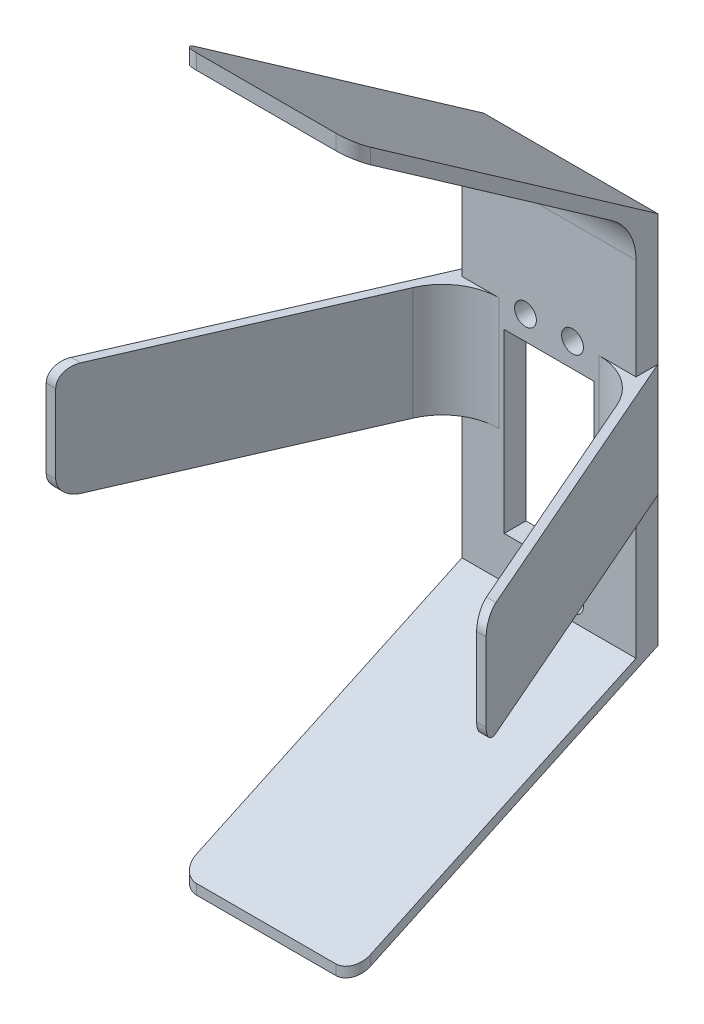
SolidWorks part; units mm, degrees
ref_plane "Plan de face" through (0, 0, 0) normal (0, 0, 1) x (1, 0, 0)
ref_plane "Plan de dessus" through (0, 0, 0) normal (0, 1, 0) x (1, 0, 0)
ref_plane "Plan de droite" through (0, 0, 0) normal (1, 0, 0) x (0, 0, -1)
sketch "Esquisse1" plane through (0, 0, 0) normal (0, 0, 1) x (1, 0, 0)
  line L8 (0.3, -20.3) -> (0.3, 20.3)
  line L9 (0.3, 20.3) -> (-20.3, 20.3)
  line L10 (-20.3, 20.3) -> (-20.3, -20.3)
  line L11 (-20.3, -20.3) -> (0.3, -20.3)
  line L12 (0.3, -20.3) -> (0.3, 20.3)
  line L13 (0.3, 20.3) -> (-20.3, 20.3)
  line L14 (-20.3, 20.3) -> (-20.3, -20.3)
  line L15 (-20.3, -20.3) -> (0.3, -20.3)
  line L20 (10, -30) -> (10, 30)
  line L21 (10, 30) -> (-30, 30)
  line L22 (-30, 30) -> (-30, -30)
  line L23 (-30, -30) -> (10, -30)
  line L24 (10, -30) -> (10, 30)
  line L25 (10, 30) -> (-30, 30)
  line L26 (-30, 30) -> (-30, -30)
  line L27 (-30, -30) -> (10, -30)
  dimension "D1" = 0.3
  dimension "D2" = 10
extrude "Boss.-Extru.1" add sketch "Esquisse1" along normal blind 5
sketch "Esquisse2" plane through (0, 30, 0) normal (0, 1, 0) x (1, 0, 0)
  line L4 (10, 0) -> (-30, 0)
  line L5 (-30, 0) -> (-30, -5)
  line L6 (-30, -5) -> (10, -5)
  line L7 (10, -5) -> (10, 0)
  line L8 (10, 0) -> (-30, 0)
  line L9 (-30, 0) -> (-30, -5)
  line L10 (-30, -5) -> (10, -5)
  line L11 (10, -5) -> (10, 0)
  dimension "D1" = 0
extrude "Boss.-Extru.2" add sketch "Esquisse2" along normal blind 26
sketch "Esquisse3" plane through (10, 0, 0) normal (1, 0, 0) x (0, 0, -1)
  line L0 (0, 56) -> (-70, 105.0145)
  line L1 (-70, 105.0145) -> (-70, 101.5135)
  line L2 (-70, 101.5135) -> (-5, 56)
  line L3 (-5, 56) -> (0, 56) construction
  line L5 (-5, 56) -> (0, 56)
  line L6 (-5, -30) -> (-5, 56) construction
  line L7 (-5, -30) -> (0, -30) construction
  line L8 (-5, -30) -> (0, -30)
  line L9 (-5, -30) -> (-70, -60.31)
  line L10 (-70, -60.31) -> (-70, -62.6415)
  line L11 (-70, -62.6415) -> (0, -30)
  point P7 (-70, 103.264)
  dimension "D1" = 125
  dimension "D2" = 65
  dimension "D3" = 115
extrude "Boss.-Extru.5" add sketch "Esquisse3" against normal up to surface (40 mm away) up to face at (-30, 13, 2.5)
sketch "Esquisse4" plane through (0, 0, 0) normal (0, 1, 0) x (1, 0, 0)
  line L0 (-30, -5) -> (-58.3683, -70)
  line L1 (-58.3683, -70) -> (-60.5505, -70)
  line L2 (-60.5505, -70) -> (-30, 0)
  line L3 (-30, -70) -> (-30, 0) construction
  line L5 (10, 0) -> (40.5505, -70)
  line L6 (40.5505, -70) -> (38.3683, -70)
  line L7 (38.3683, -70) -> (10, -5)
  line L8 (10, -5) -> (10, 0)
  line L9 (-30, -70) -> (10, -70) construction
  line L10 (-30, 0) -> (-30, -5)
  line L11 (10, 0) -> (-30, 0) construction
  point P15 (0, 0)
  dimension "D1" = 2
  dimension "D2" = 2
extrude "Boss.-Extru.6" add sketch "Esquisse4" along normal blind 26
fillet "Congé1" radius 13 3 edges at (-10, 56, 5) (10, 13, 5) (-30, 13, 5)
fillet "Congé2" radius 4 8 edges at (-59.4594, 0, 70) (-59.4594, 26, 70) (-30, 103.264, 70) (10, 103.264, 70) (39.4594, 26, 70) (39.4594, 0, 70) (-30, -61.4758, 70) (10, -61.4758, 70)
sketch "Esquisse6" plane through (0, 0, 0) normal (0, 0, -1) x (-1, 0, 0)
  arc A0 (5.7874, -28) -> (3.4126, -28) centre (4.6, -25.8) ccw construction
  arc A1 (16.5874, -28) -> (14.2126, -28) centre (15.4, -25.8) ccw construction
  arc A2 (3.4126, 28) -> (5.7874, 28) centre (4.6, 25.8) ccw construction
  arc A3 (14.2126, 28) -> (16.5874, 28) centre (15.4, 25.8) ccw construction
  circle A4 centre (4.6, -25.8) radius 2.5
  circle A5 centre (15.4, -25.8) radius 2.5
  circle A6 centre (4.6, 25.8) radius 2.5
  circle A7 centre (15.4, 25.8) radius 2.5
  point P12 (3.5444, -28)
  point P14 (16.4441, -28)
  point P16 (16.4535, 28)
  point P18 (5.7043, 28)
extrude "Enlèv. mat.-Extru.1" cut sketch "Esquisse6" against normal up to next
